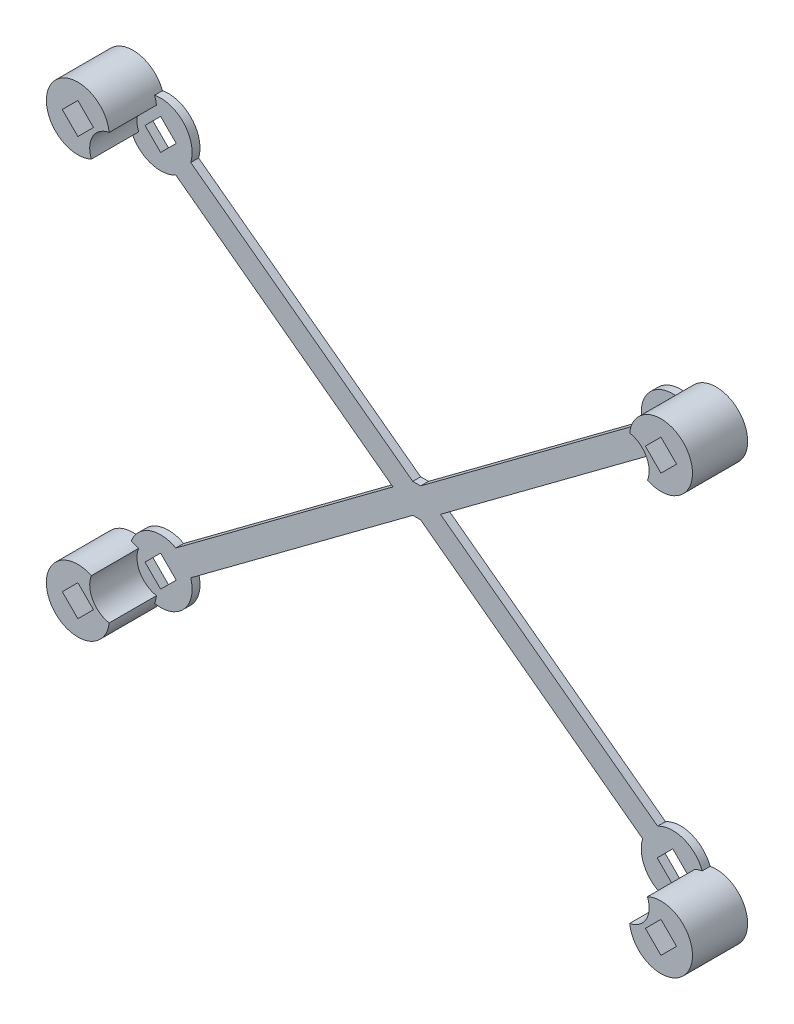
SolidWorks part; units mm, degrees
ref_plane "Plano frontal" through (0, 0, 0) normal (0, 0, 1) x (1, 0, 0)
ref_plane "Plano superior" through (0, 0, 0) normal (0, 1, 0) x (1, 0, 0)
ref_plane "Plano direito" through (0, 0, 0) normal (1, 0, 0) x (0, 0, -1)
sketch "Esboço1" plane through (0, 0, 0) normal (0, 0, 1) x (1, 0, 0)
  line L0 (-39, 29) -> (-39, 26.5) construction
  line L1 (-38.4799, -26.5) -> (-34.5201, -26.5) construction
  line L2 (0, 1.8692) -> (-27.9936, 22.685)
  line L3 (-32, 0) -> (-39, 0) construction
  line L4 (-38.4799, 26.5) -> (-36.5, 28.4799)
  line L5 (-39, 29) -> (0, 0) construction
  line L6 (-38.4799, 26.5) -> (-36.5, 24.5201)
  line L7 (-39, 26.5) -> (-36.5, 26.5) construction
  line L8 (-36.5, 24.5201) -> (-36.5, 28.4799) construction
  line L9 (0.5, -1.8692) -> (0.5, 1.8692) construction
  line L10 (0, 1.8692) -> (1, 1.8692) construction
  line L11 (-32, -24) -> (-32, 24) construction
  line L12 (-33.9799, 24) -> (-32, 25.9799)
  line L13 (-33.9799, 24) -> (-32, 22.0201)
  line L14 (-32, 22.0201) -> (-30.0201, 24)
  line L15 (-32, 25.9799) -> (-30.0201, 24)
  line L16 (-33.9799, 24) -> (-30.0201, 24) construction
  line L17 (-32, 22.0201) -> (-32, 25.9799) construction
  line L18 (-36.5, 24.5201) -> (-34.5201, 26.5)
  line L19 (-36.5, 28.4799) -> (-34.5201, 26.5)
  line L20 (-38.4799, 26.5) -> (-34.5201, 26.5) construction
  line L21 (-2.5138, 0) -> (-29.7837, 20.2776)
  line L22 (-27.9936, 22.685) -> (-28.1775, 22.8217)
  line L23 (-32, -22.0201) -> (-32, -25.9799) construction
  line L24 (-29.7837, 20.2776) -> (-30.0746, 20.4939)
  line L25 (-33.9799, -24) -> (-30.0201, -24) construction
  line L26 (-36.5, -24.5201) -> (-36.5, -28.4799) construction
  line L27 (-39, -26.5) -> (-36.5, -26.5) construction
  line L28 (-39, -29) -> (0, 0) construction
  line L29 (-39, -29) -> (-39, -26.5) construction
  line L30 (-29.7837, -20.2776) -> (-30.0746, -20.4939)
  line L31 (-27.9936, -22.685) -> (-28.1775, -22.8217)
  line L32 (-2.5138, 0) -> (-29.7837, -20.2776)
  line L33 (-36.5, -28.4799) -> (-34.5201, -26.5)
  line L34 (-36.5, -24.5201) -> (-34.5201, -26.5)
  line L35 (-32, -25.9799) -> (-30.0201, -24)
  line L36 (-32, -22.0201) -> (-30.0201, -24)
  line L37 (-33.9799, -24) -> (-32, -22.0201)
  line L38 (-33.9799, -24) -> (-32, -25.9799)
  line L39 (-38.4799, -26.5) -> (-36.5, -24.5201)
  line L40 (-38.4799, -26.5) -> (-36.5, -28.4799)
  line L41 (0, -1.8692) -> (-27.9936, -22.685)
  line L42 (0, -1.8692) -> (1, -1.8692)
  line L43 (0.5, 1.8692) -> (0.5, 10.6407) construction
  line L44 (40, -29) -> (40, -26.5) construction
  line L45 (40, -29) -> (1, 0) construction
  line L46 (40, -26.5) -> (37.5, -26.5) construction
  line L47 (37.5, -24.5201) -> (37.5, -28.4799) construction
  line L48 (34.9799, -24) -> (31.0201, -24) construction
  line L49 (33, -22.0201) -> (33, -25.9799) construction
  line L50 (39.4799, 26.5) -> (35.5201, 26.5) construction
  line L51 (33, 22.0201) -> (33, 25.9799) construction
  line L52 (34.9799, 24) -> (31.0201, 24) construction
  line L53 (33, -24) -> (33, 24) construction
  line L54 (37.5, 24.5201) -> (37.5, 28.4799) construction
  line L55 (40, 26.5) -> (37.5, 26.5) construction
  line L56 (40, 29) -> (1, 0) construction
  line L57 (33, 0) -> (40, 0) construction
  line L58 (39.4799, -26.5) -> (35.5201, -26.5) construction
  line L59 (40, 29) -> (40, 26.5) construction
  line L60 (1, -1.8692) -> (28.9936, -22.685)
  line L61 (39.4799, -26.5) -> (37.5, -28.4799)
  line L62 (39.4799, -26.5) -> (37.5, -24.5201)
  line L63 (34.9799, -24) -> (33, -25.9799)
  line L64 (34.9799, -24) -> (33, -22.0201)
  line L65 (33, -22.0201) -> (31.0201, -24)
  line L66 (33, -25.9799) -> (31.0201, -24)
  line L67 (37.5, -24.5201) -> (35.5201, -26.5)
  line L68 (37.5, -28.4799) -> (35.5201, -26.5)
  line L69 (3.5138, 0) -> (30.7837, -20.2776)
  line L70 (28.9936, -22.685) -> (29.1775, -22.8217)
  line L71 (30.7837, -20.2776) -> (31.0746, -20.4939)
  line L72 (30.7837, 20.2776) -> (31.0746, 20.4939)
  line L73 (28.9936, 22.685) -> (29.1775, 22.8217)
  line L74 (3.5138, 0) -> (30.7837, 20.2776)
  line L75 (37.5, 28.4799) -> (35.5201, 26.5)
  line L76 (37.5, 24.5201) -> (35.5201, 26.5)
  line L77 (33, 25.9799) -> (31.0201, 24)
  line L78 (33, 22.0201) -> (31.0201, 24)
  line L79 (34.9799, 24) -> (33, 22.0201)
  line L80 (34.9799, 24) -> (33, 25.9799)
  line L81 (39.4799, 26.5) -> (37.5, 24.5201)
  line L82 (39.4799, 26.5) -> (37.5, 28.4799)
  line L83 (1, 1.8692) -> (28.9936, 22.685)
  line L84 (0, 1.8692) -> (1, 1.8692)
  arc A0 (-32.763, 27.9265) -> (-35.737, 22.5735) centre (-36.5, 26.5) ccw
  arc A1 (-28.1775, 22.8217) -> (-32.763, 27.9265) centre (-32, 24) ccw
  arc A2 (-35.737, 22.5735) -> (-30.0746, 20.4939) centre (-32, 24) ccw
  arc A3 (-35.737, -22.5735) -> (-30.0746, -20.4939) centre (-32, -24) cw
  arc A4 (-28.1775, -22.8217) -> (-32.763, -27.9265) centre (-32, -24) cw
  arc A5 (-32.763, -27.9265) -> (-35.737, -22.5735) centre (-36.5, -26.5) cw
  arc A6 (33.763, -27.9265) -> (36.737, -22.5735) centre (37.5, -26.5) ccw
  arc A7 (29.1775, -22.8217) -> (33.763, -27.9265) centre (33, -24) ccw
  arc A8 (36.737, -22.5735) -> (31.0746, -20.4939) centre (33, -24) ccw
  arc A9 (36.737, 22.5735) -> (31.0746, 20.4939) centre (33, 24) cw
  arc A10 (29.1775, 22.8217) -> (33.763, 27.9265) centre (33, 24) cw
  arc A11 (33.763, 27.9265) -> (36.737, 22.5735) centre (37.5, 26.5) cw
  point P0 (0, 0)
  point P3 (-36.5, 26.5)
  point P7 (-32, 24)
  dimension "D5" = 24
  dimension "D3" = 2.5
  dimension "D4" = 2.5
  dimension "D6" = 32
  dimension "D7" = 2.8
extrude "Ressalto-extrusão1" add sketch "Esboço1" along normal blind 1
sketch "Esboço3" plane through (0, 0, 1) normal (0, 0, 1) x (1, 0, 0)
  line L0 (-37.4899, 25.5101) -> (-35.5101, 27.4899) construction
  line L1 (-38.4799, 26.5) -> (-36.5, 24.5201) construction
  line L2 (-34.5201, 26.5) -> (-36.5, 28.4799) construction
  line L3 (-36.5, 28.4799) -> (-38.4799, 26.5) construction
  line L4 (-36.5, 24.5201) -> (-34.5201, 26.5) construction
  line L5 (-38.4799, 26.5) -> (-36.5, 24.5201)
  line L6 (-36.5, 28.4799) -> (-38.4799, 26.5)
  line L7 (-34.5201, 26.5) -> (-36.5, 28.4799)
  line L8 (-36.5, 24.5201) -> (-34.5201, 26.5)
  line L9 (-32.9899, 23.0101) -> (-31.0101, 24.9899) construction
  line L10 (-33.9799, 24) -> (-32, 22.0201) construction
  line L11 (-30.0201, 24) -> (-32, 25.9799) construction
  line L12 (0, 0) -> (-26.3009, 0) construction
  line L13 (-26.3009, 0) -> (0, 0) construction
  line L14 (0.5, 1.8692) -> (0.5, -1.8692) construction
  line L15 (-32.9899, -23.0101) -> (-31.0101, -24.9899) construction
  line L16 (-37.4899, -25.5101) -> (-35.5101, -27.4899) construction
  line L17 (-36.5, -24.5201) -> (-34.5201, -26.5)
  line L18 (-34.5201, -26.5) -> (-36.5, -28.4799)
  line L19 (-36.5, -28.4799) -> (-38.4799, -26.5)
  line L20 (-38.4799, -26.5) -> (-36.5, -24.5201)
  line L21 (1, 1.8692) -> (0, 1.8692) construction
  line L22 (0, -1.8692) -> (1, -1.8692) construction
  line L23 (0.5, -1.8692) -> (0.5, 1.8692) construction
  line L24 (0.5, 1.8692) -> (0.5, 33.9244) construction
  line L25 (38.4899, -25.5101) -> (36.5101, -27.4899) construction
  line L26 (33.9899, -23.0101) -> (32.0101, -24.9899) construction
  line L27 (27.3009, 0) -> (1, 0) construction
  line L28 (1, 0) -> (27.3009, 0) construction
  line L29 (33.9899, 23.0101) -> (32.0101, 24.9899) construction
  line L30 (38.4899, 25.5101) -> (36.5101, 27.4899) construction
  line L31 (39.4799, -26.5) -> (37.5, -24.5201)
  line L32 (37.5, -28.4799) -> (39.4799, -26.5)
  line L33 (35.5201, -26.5) -> (37.5, -28.4799)
  line L34 (37.5, -24.5201) -> (35.5201, -26.5)
  line L35 (37.5, 24.5201) -> (35.5201, 26.5)
  line L36 (35.5201, 26.5) -> (37.5, 28.4799)
  line L37 (37.5, 28.4799) -> (39.4799, 26.5)
  line L38 (39.4799, 26.5) -> (37.5, 24.5201)
  arc A0 (-32.5258, 26.9536) -> (-34.7855, 22.8861) centre (-36.5, 26.5) ccw
  arc A1 (-32.5258, 26.9536) -> (-34.7855, 22.8861) centre (-32, 24) ccw
  arc A2 (-32.5258, -26.9536) -> (-34.7855, -22.8861) centre (-32, -24) cw
  arc A3 (-32.5258, -26.9536) -> (-34.7855, -22.8861) centre (-36.5, -26.5) cw
  arc A4 (33.5258, -26.9536) -> (35.7855, -22.8861) centre (37.5, -26.5) ccw
  arc A5 (33.5258, -26.9536) -> (35.7855, -22.8861) centre (33, -24) ccw
  arc A6 (33.5258, 26.9536) -> (35.7855, 22.8861) centre (33, 24) cw
  arc A7 (33.5258, 26.9536) -> (35.7855, 22.8861) centre (37.5, 26.5) cw
  point P6 (-36.5, 26.5)
extrude "Ressalto-extrusão3" add sketch "Esboço3" along normal blind 6
